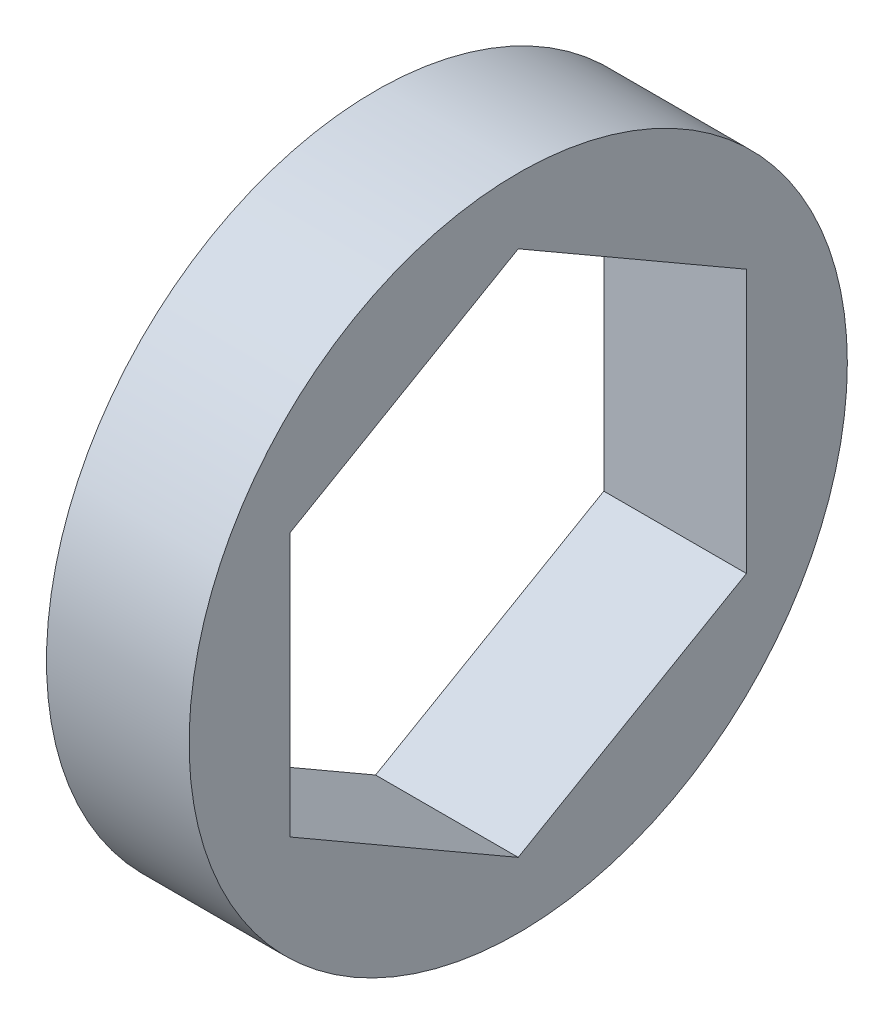
SolidWorks part; units mm, degrees
material "ABS"
ref_plane "Front Plane" through (0, 0, 0) normal (0, 0, 1) x (1, 0, 0)
ref_plane "Top Plane" through (0, 0, 0) normal (0, 1, 0) x (1, 0, 0)
ref_plane "Right Plane" through (0, 0, 0) normal (1, 0, 0) x (0, 0, -1)
sketch "Sketch1" plane through (0, 0, 0) normal (1, 0, 0) x (0, 0, -1)
  line L1 (0, 7.6256) -> (-6.604, 3.8128)
  line L2 (-6.604, 3.8128) -> (-6.604, -3.8128)
  line L3 (-6.604, -3.8128) -> (0, -7.6256)
  line L4 (0, -7.6256) -> (6.604, -3.8128)
  line L5 (6.604, -3.8128) -> (6.604, 3.8128)
  line L6 (6.604, 3.8128) -> (0, 7.6256)
  circle A0 centre (0, 0) radius 9.525
  circle A1 centre (0, 0) radius 6.604 construction
  dimension "D1" = 13.208
  dimension "D2" = 19.05
extrude "Boss-Extrude1" add sketch "Sketch1" along normal blind 4.1275
